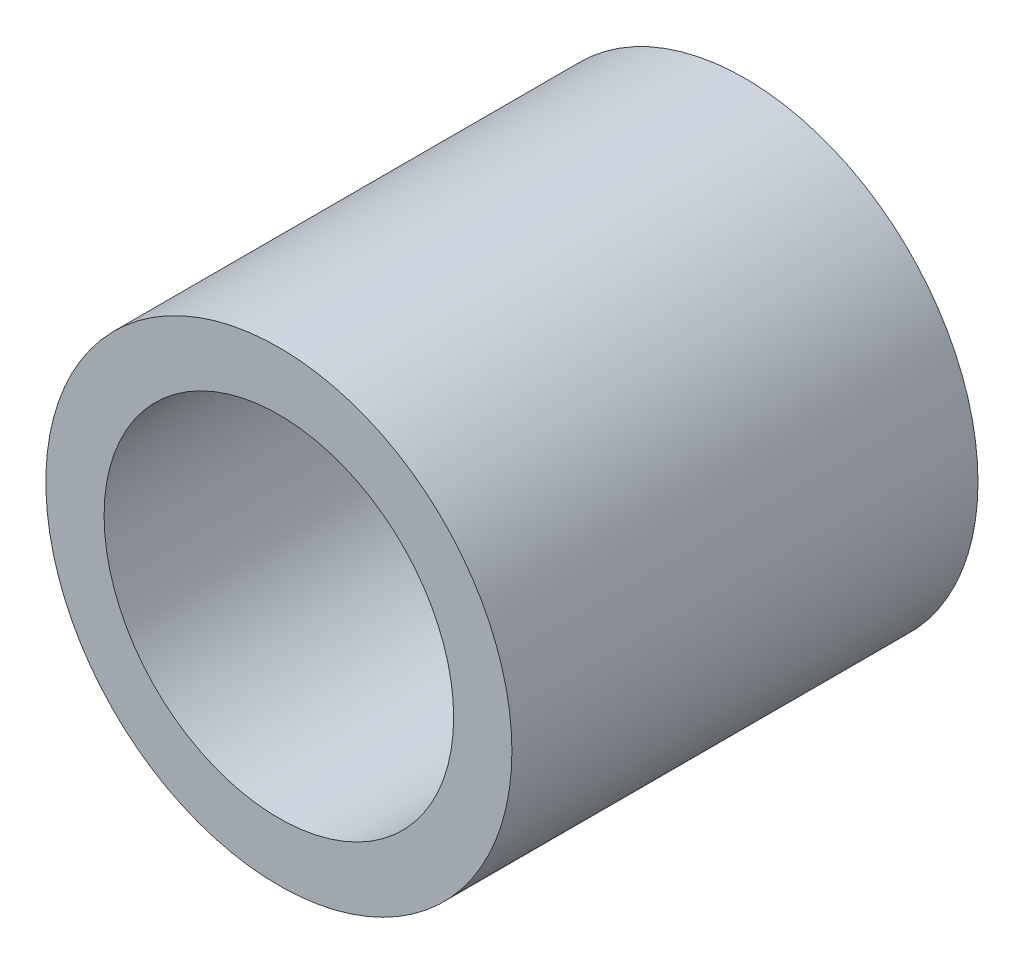
SolidWorks part; units mm, degrees
ref_plane "前视基准面" through (0, 0, 0) normal (0, 0, 1) x (1, 0, 0)
ref_plane "上视基准面" through (0, 0, 0) normal (0, 1, 0) x (1, 0, 0)
ref_plane "右视基准面" through (0, 0, 0) normal (1, 0, 0) x (0, 0, -1)
other "Configuration Table"
sketch "草图1" plane through (0, 0, 0) normal (0, 0, 1) x (1, 0, 0)
  circle A0 centre (0, 0) radius 3.75
  circle A1 centre (0, 0) radius 5
  dimension "D1" = 10
  dimension "7.5" = 7.5
extrude "凸台-拉伸1" add sketch "草图1" along normal blind 10
